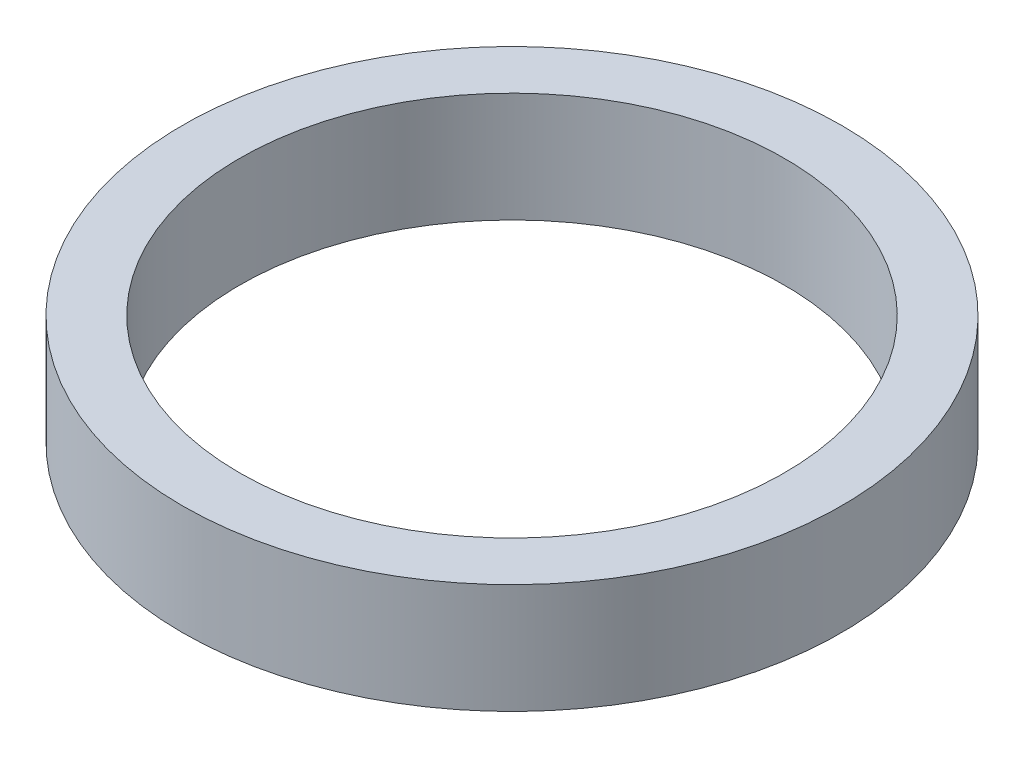
SolidWorks part; units mm, degrees
ref_plane "Front Plane" through (0, 0, 0) normal (0, 0, 1) x (1, 0, 0)
ref_plane "Top Plane" through (0, 0, 0) normal (0, 1, 0) x (1, 0, 0)
ref_plane "Right Plane" through (0, 0, 0) normal (1, 0, 0) x (0, 0, -1)
sketch "Sketch1" plane through (0, 0, 0) normal (0, 1, 0) x (1, 0, 0)
  circle A0 centre (0, 0) radius 3.1
  circle A1 centre (0, 0) radius 3.75
  dimension "D1" = 6.2
  dimension "D2" = 7.5
extrude "Boss-Extrude1" add sketch "Sketch1" along normal blind 1.25
